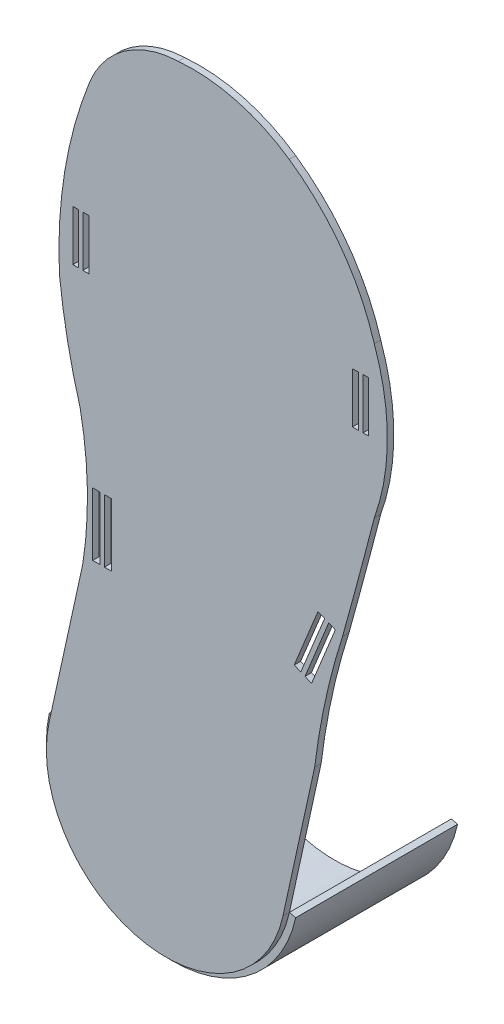
SolidWorks part; units mm, degrees
ref_plane "Front Plane" through (0, 0, 0) normal (0, 0, 1) x (1, 0, 0)
ref_plane "Top Plane" through (0, 0, 0) normal (0, 1, 0) x (1, 0, 0)
ref_plane "Right Plane" through (0, 0, 0) normal (1, 0, 0) x (0, 0, -1)
sketch "Sketch1" plane through (0, 0, 0) normal (0, 0, 1) x (1, 0, 0)
  line L0 (746.4018, 685.1437) -> (1343.7351, 685.1437) construction
  line L1 (-51.9841, 392.7496) -> (0, 630.0981)
  line L2 (308.9904, 313.6889) -> (358.0638, 537.7476)
  arc A0 (-51.9841, 392.7496) -> (308.9904, 313.6889) centre (128.5031, 353.2192) ccw
  arc A1 (0, 630.0981) -> (-3.9841, 836.2782) centre (-582.9992, 721.9612) ccw
  arc A2 (358.0638, 537.7476) -> (400.9081, 733.3643) centre (1416.031, 408.5298) cw
  arc A3 (-3.9841, 836.2782) -> (-36.0126, 998.5024) centre (912.2213, 1101.4418) cw
  arc A4 (-36.0126, 998.5024) -> (10.5352, 1279.7162) centre (634.3449, 1032.001) cw
  arc A5 (400.9081, 733.3643) -> (450.0332, 916.6956) centre (-9292.1389, 3428.9398) ccw
  arc A6 (450.0332, 916.6956) -> (450.0332, 1149.5484) centre (124.6316, 1033.122) ccw
  arc A7 (450.0332, 1149.5484) -> (318.8388, 1330.4675) centre (127.1501, 1053.4358) ccw
  arc A8 (10.5352, 1279.7162) -> (147.4353, 1375.9125) centre (152.355, 1223.3994) cw
  arc A9 (147.4353, 1375.9125) -> (318.8388, 1330.4675) centre (170.1313, 1115.5528) cw
  dimension "D3" = 1065.8292
  dimension "D4" = 10060.8791
  dimension "D5" = 509.7133
  dimension "D6" = 336.8844
  dimension "D1" = 369.531
  dimension "D2" = 224.0587
extrude "Boss-Extrude1" add sketch "Sketch1" along normal blind 10
sketch "Sketch2" plane through (0, 0, 0) normal (0, 0, -1) x (-1, 0, 0)
  line L0 (-318.7588, 311.5494) -> (-308.9904, 313.6889)
  line L1 (51.9841, 392.7496) -> (61.7526, 394.8891)
  arc A0 (-308.9904, 313.6889) -> (51.9841, 392.7496) centre (-128.5031, 353.2192) ccw
  arc A1 (-318.7588, 311.5494) -> (61.7526, 394.8891) centre (-128.5031, 353.2192) ccw
  dimension "D1" = 10
extrude "Boss-Extrude2" add sketch "Sketch2" along normal blind 250 separate body
sketch "Sketch3" plane through (0, 0, 0) normal (0, 0, -1) x (-1, 0, 0)
  line L1 (0, 1100.7189) -> (-9.5652, 1100.7189)
  line L2 (0, 1100.7189) -> (0, 1022.7525)
  line L3 (0, 1022.7525) -> (-9.5652, 1022.7525)
  line L4 (-9.5652, 1100.7189) -> (-9.5652, 1022.7525)
  line L5 (7, 1100.7189) -> (15.3535, 1100.7189)
  line L6 (7, 1100.7189) -> (7, 1022.7525)
  line L7 (7, 1022.7525) -> (15.3535, 1022.7525)
  line L8 (15.3535, 1100.7189) -> (15.3535, 1022.7525)
  line L9 (-441.1961, 1099.8605) -> (-441.1961, 1021.894)
  line L10 (-432.8425, 1021.894) -> (-441.1961, 1021.894)
  line L11 (-432.8425, 1099.8605) -> (-432.8425, 1021.894)
  line L12 (-432.8425, 1099.8605) -> (-441.1961, 1099.8605)
  line L13 (-416.2773, 1099.4312) -> (-416.2773, 1021.4648)
  line L14 (-425.8425, 1021.4648) -> (-416.2773, 1021.4648)
  line L15 (-425.8425, 1099.4312) -> (-425.8425, 1021.4648)
  line L16 (-425.8425, 1099.4312) -> (-416.2773, 1099.4312)
  dimension "D1" = 7
  dimension "D2" = 7
extrude "Cut-Extrude1" cut sketch "Sketch3" against normal blind 250
sketch "Sketch4" plane through (0, 0, 0) normal (0, 0, -1) x (-1, 0, 0)
  line L0 (-44.333, 642.5598) -> (-33.333, 642.5598)
  line L1 (-26.333, 739.5598) -> (-15.333, 739.5598)
  line L2 (-26.333, 739.5598) -> (-26.333, 642.5598)
  line L4 (-15.333, 739.5598) -> (-15.333, 642.5598)
  line L5 (-33.333, 739.5598) -> (-44.333, 739.5598)
  line L6 (-33.333, 739.5598) -> (-33.333, 642.5598)
  line L8 (-44.333, 739.5598) -> (-44.333, 642.5598)
  line L9 (-363.1242, 747.9664) -> (-326.394, 658.1895)
  line L10 (-336.5749, 654.0242) -> (-326.394, 658.1895)
  line L11 (-373.3051, 743.8011) -> (-336.5749, 654.0242)
  line L12 (-373.3051, 743.8011) -> (-363.1242, 747.9664)
  line L13 (-389.9522, 736.9547) -> (-353.222, 647.1778)
  line L14 (-343.0412, 651.343) -> (-353.222, 647.1778)
  line L15 (-379.7713, 741.1199) -> (-343.0412, 651.343)
  line L16 (-379.7713, 741.1199) -> (-389.9522, 736.9547)
  line L17 (-26.333, 642.5598) -> (-15.333, 642.5598)
  dimension "D1" = 97
  dimension "D2" = 97
  dimension "D3" = 11
  dimension "D4" = 11
  dimension "D5" = 7
  dimension "D6" = 7
extrude "Cut-Extrude2" cut sketch "Sketch4" against normal blind 250
